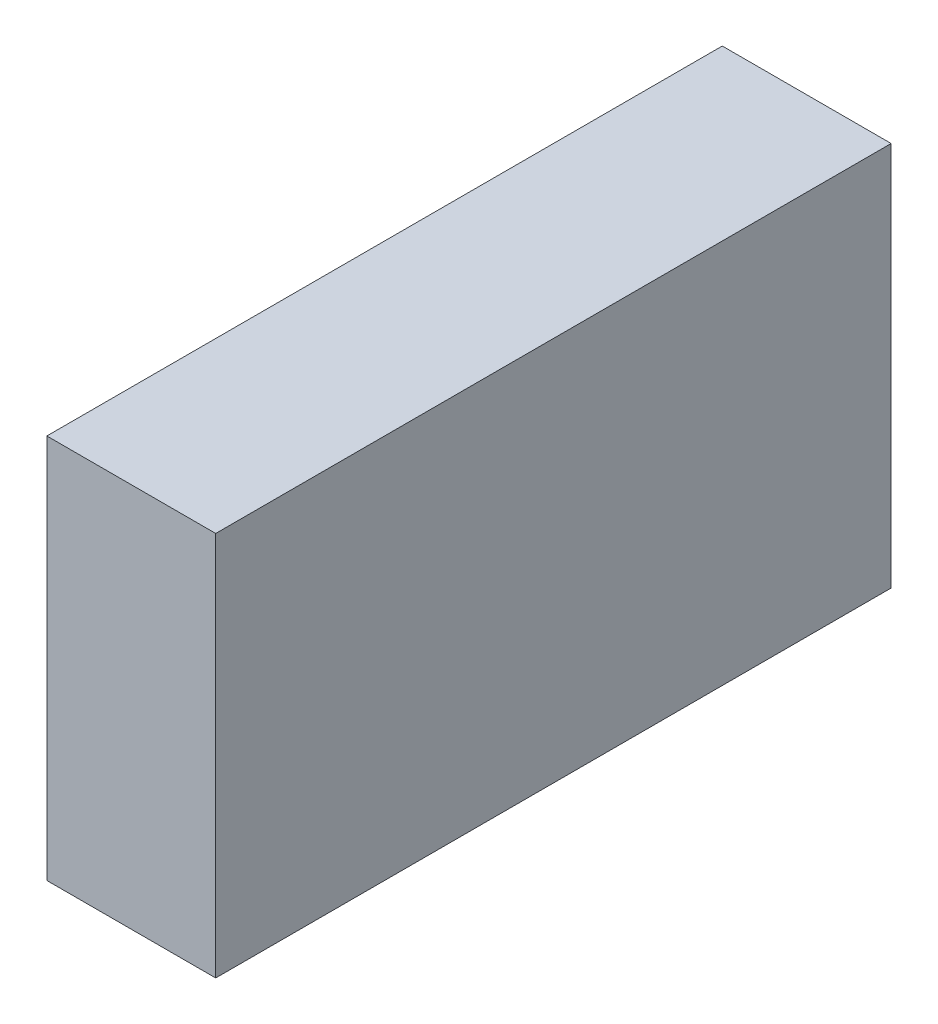
SolidWorks part; units mm, degrees
material "Porcelana cerâmica"
ref_plane "Plano frontal" through (0, 0, 0) normal (0, 0, 1) x (1, 0, 0)
ref_plane "Plano superior" through (0, 0, 0) normal (0, 1, 0) x (1, 0, 0)
ref_plane "Plano direito" through (0, 0, 0) normal (1, 0, 0) x (0, 0, -1)
sketch "Esboço1" plane through (0, 0, 0) normal (0, 0, 1) x (1, 0, 0)
  line L1 (0, 0) -> (50, 0)
  line L2 (0, 0) -> (0, 114)
  line L3 (0, 114) -> (50, 114)
  line L4 (50, 0) -> (50, 114)
  dimension "D1" = 114
  dimension "D2" = 50
extrude "Ressalto-extrusão1" add sketch "Esboço1" along normal blind 200
